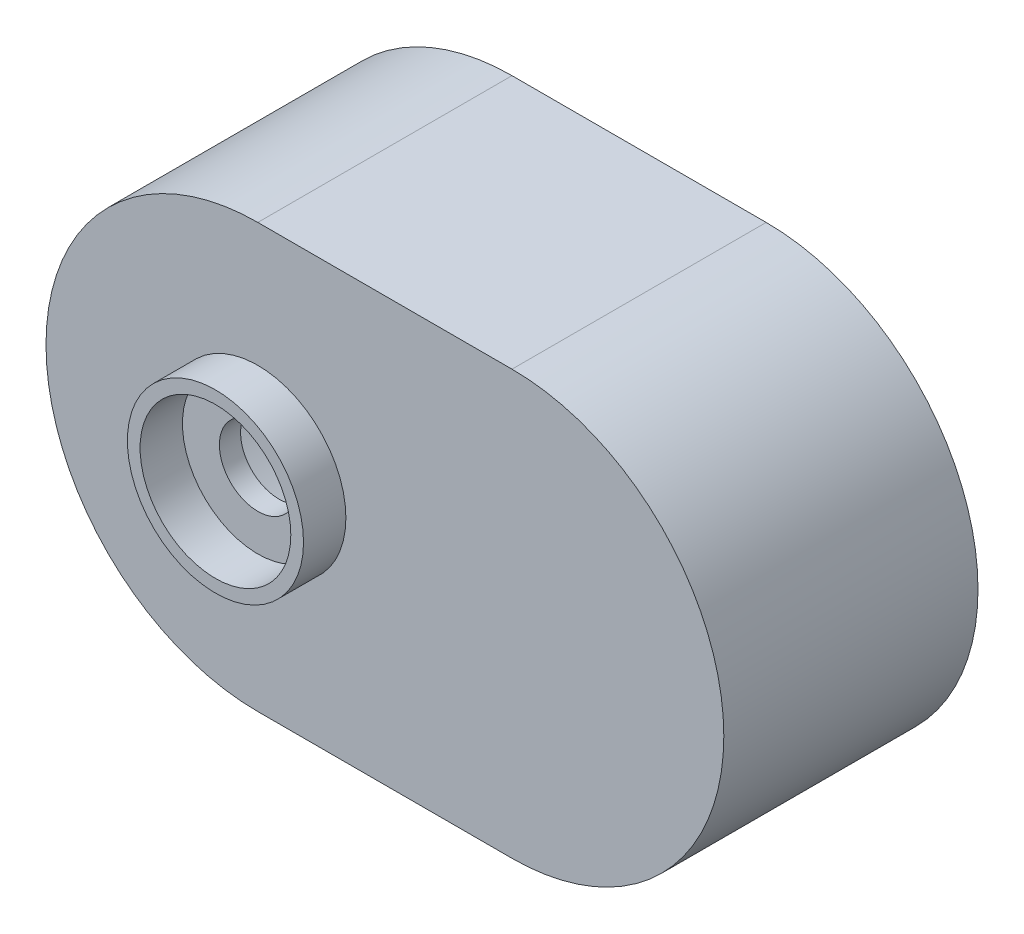
SolidWorks part; units mm, degrees
ref_plane "前视基准面" through (0, 0, 0) normal (0, 0, 1) x (1, 0, 0)
ref_plane "上视基准面" through (0, 0, 0) normal (0, 1, 0) x (1, 0, 0)
ref_plane "右视基准面" through (0, 0, 0) normal (1, 0, 0) x (0, 0, -1)
other "Configuration Table"
sketch "草图1" plane through (0, 0, 0) normal (0, 0, 1) x (1, 0, 0)
  line L0 (0, 0) -> (60, 0) construction
  line L1 (0, 50) -> (60, 50)
  line L2 (0, -50) -> (60, -50)
  arc A0 (0, 50) -> (0, -50) centre (0, 0) ccw
  arc A1 (60, -50) -> (60, 50) centre (60, 0) ccw
  point P3 (30, 0)
  point P8 (0, 0)
  point P10 (40.1191, 46.4302)
  dimension "D1" = 50
  dimension "D2" = 60
extrude "凸台-拉伸1" add sketch "草图1" along normal blind 60
sketch "草图2" plane through (0, 0, 0) normal (0, 0, -1) x (-1, 0, 0)
  line L0 (-60, 50) -> (0, 50) construction
  line L1 (-60, 50) -> (0, 50)
  line L2 (-60, -47) -> (0, -47)
  line L3 (0, 47) -> (-60, 47)
  line L4 (0, 50) -> (-60, 50)
  line L5 (-60, -50) -> (0, -50)
  line L6 (0, 50) -> (-60, 50)
  line L7 (-60, -50) -> (0, -50)
  arc A0 (0, -50) -> (0, 50) centre (0, 0) ccw construction
  arc A1 (0, -50) -> (0, 50) centre (0, 0) ccw
  arc A2 (-60, 47) -> (-60, -47) centre (-60, 0) ccw
  arc A3 (0, -47) -> (0, 47) centre (0, 0) ccw
  arc A4 (0, -50) -> (0, 50) centre (0, 0) ccw
  arc A5 (-60, 50) -> (-60, -50) centre (-60, 0) ccw
  arc A6 (0, -50) -> (0, 50) centre (0, 0) ccw
  arc A7 (-60, 50) -> (-60, -50) centre (-60, 0) ccw
  dimension "D1" = 0
  dimension "D2" = 3
extrude "切除-拉伸1" cut sketch "草图2" against normal blind 55 contours L2 A3 L3 A2
sketch "草图3" plane through (0, 0, 60) normal (0, 0, 1) x (1, 0, 0)
  circle A0 centre (0, 0) radius 20.7891
  circle A2 centre (0, 0) radius 17.7891
  dimension "D1" = 3
extrude "凸台-拉伸2" add sketch "草图3" along normal blind 10 contours A0 A2
sketch "草图4" plane through (0, 0, 60) normal (0, 0, 1) x (1, 0, 0)
  circle A0 centre (0, 0) radius 9.0722
sketch "草图6" plane through (0, 0, 60) normal (0, 0, 1) x (1, 0, 0)
extrude "切除-拉伸5" cut sketch "草图4" against normal through all
sketch "草图7" plane through (0, 0, 55) normal (0, 0, -1) x (-1, 0, 0)
  circle A0 centre (0, 0) radius 20
  circle A1 centre (-43.8734, 2.2968) radius 15
  point P5 (-31.7904, -0.5992)
  dimension "D1" = 30
  dimension "D2" = 40
